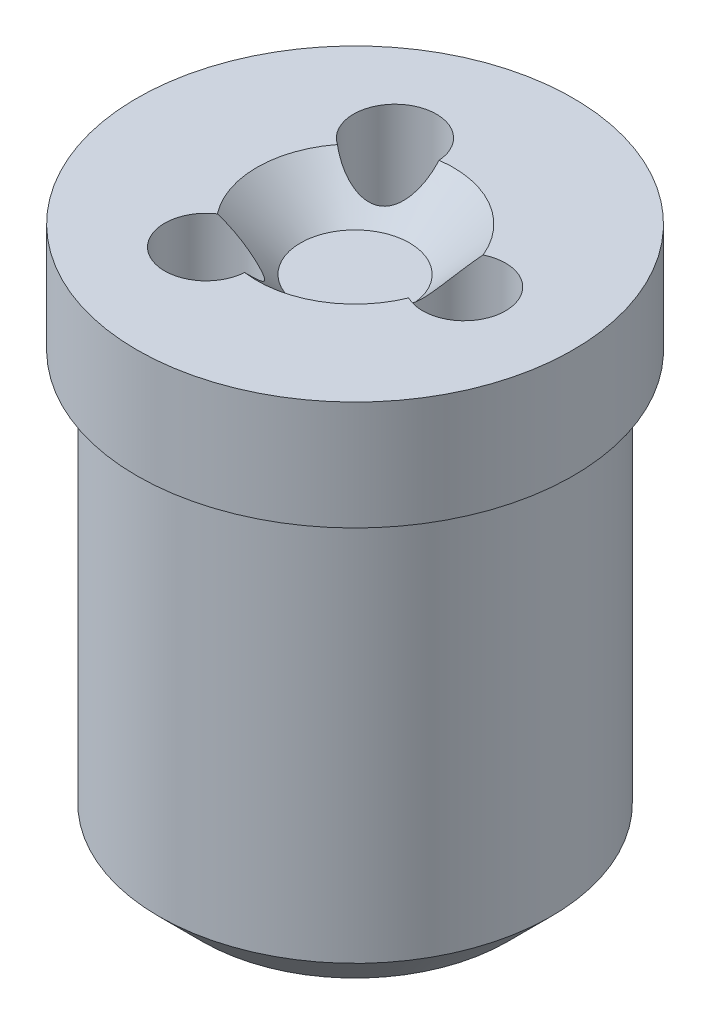
SolidWorks part; units mm, degrees
material "ABS"
ref_plane "前视基准面" through (0, 0, 0) normal (0, 0, 1) x (1, 0, 0)
ref_plane "上视基准面" through (0, 0, 0) normal (0, 1, 0) x (1, 0, 0)
ref_plane "右视基准面" through (0, 0, 0) normal (1, 0, 0) x (0, 0, -1)
sketch "草图1" plane through (0, 0, 0) normal (0, 1, 0) x (1, 0, 0)
  circle A0 centre (0, 0) radius 8.99
  dimension "D1" = 17.98
extrude "凸台-拉伸1" add sketch "草图1" along normal blind 20
sketch "草图2" plane through (0, 20, 0) normal (0, 1, 0) x (1, 0, 0)
  circle A0 centre (0, 0) radius 10
  dimension "D1" = 20
extrude "凸台-拉伸2" add sketch "草图2" along normal blind 5
chamfer "倒角1" distance 2 angle 45 1 edges at (0, 0, 8.99)
sketch "草图3" plane through (0, 25, 0) normal (0, 1, 0) x (1, 0, 0)
  line L1 (5, 0) -> (-2.5, 4.3301) construction
  line L2 (-2.5, 4.3301) -> (-2.5, -4.3301) construction
  line L3 (-2.5, -4.3301) -> (5, 0) construction
  circle A0 centre (0, 0) radius 5 construction
  circle A1 centre (5, 0) radius 1.9
  circle A2 centre (-2.5, -4.3301) radius 1.9
  circle A3 centre (-2.5, 4.3301) radius 1.9
  dimension "D1" = 10
  dimension "D2" = 3.8
  dimension "D3" = 3.8
  dimension "D4" = 3.8
extrude "切除-拉伸1" cut sketch "草图3" against normal blind 36
sketch "草图5" plane through (0, 0, 0) normal (0, 0, 1) x (1, 0, 0)
  line L0 (0, 0) -> (0, 31.4098) construction
  line L5 (0, 23) -> (-2.5, 23)
  line L6 (-2.5, 23) -> (-5.7808, 26.2808)
  line L7 (-5.7808, 26.2808) -> (0, 26.2808)
  line L8 (0, 26.2808) -> (0, 23)
  line L9 (10, 25) -> (-10, 25) construction
  dimension "D1" = 2
  dimension "D2" = 135
  dimension "D3" = 2.5
revolve "切除-旋转1" cut sketch "草图5" angle 360 about L0
